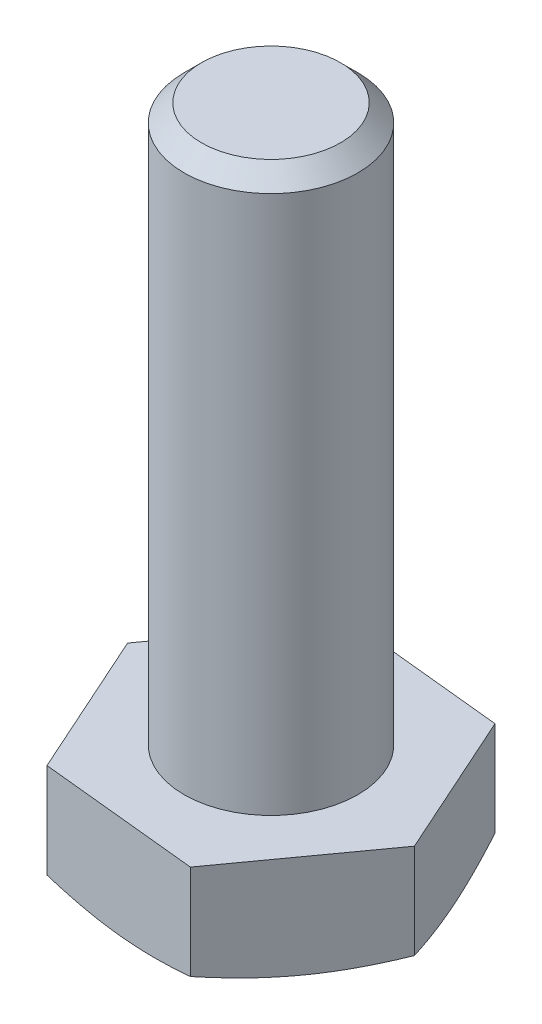
SolidWorks part; units mm, degrees
material "Plain Carbon Steel"
ref_plane "Спереди" through (0, 0, 0) normal (0, 0, 1) x (1, 0, 0)
ref_plane "Сверху" through (0, 0, 0) normal (0, 1, 0) x (1, 0, 0)
ref_plane "Справа" through (0, 0, 0) normal (1, 0, 0) x (0, 0, -1)
sketch "Sketch1" plane through (0, 0, 0) normal (0, 1, 0) x (1, 0, 0)
  circle A0 centre (0, 0) radius 2.5
  dimension "D1" = 5
extrude "Boss-Extrude1" add sketch "Sketch1" along normal blind 16
chamfer "Chamfer1" distance 0.5 angle 45 1 edges at (0, 16, 2.5)
sketch "Sketch2" plane through (0, 0, 0) normal (0, -1, 0) x (1, 0, 0)
  line L1 (4.5951, 0.4675) -> (1.8926, 4.2132)
  line L2 (1.8926, 4.2132) -> (-2.7024, 3.7457)
  line L3 (-2.7024, 3.7457) -> (-4.5951, -0.4675)
  line L4 (-4.5951, -0.4675) -> (-1.8926, -4.2132)
  line L5 (-1.8926, -4.2132) -> (2.7024, -3.7457)
  line L6 (2.7024, -3.7457) -> (4.5951, 0.4675)
  circle A0 centre (0, 0) radius 4 construction
  dimension "D1" = 8
extrude "Boss-Extrude2" add sketch "Sketch2" along normal blind 3.5
sketch "Sketch4" plane through (0, 0, 0) normal (1, 0, 0) x (0, 0, -1)
  line L0 (0, 0) -> (0, -3.5) construction
  line L1 (0, -3.5) -> (2.5, -3.5)
  line L2 (2.5, -3.5) -> (6.1938, -2.1556)
  line L3 (6.1938, -2.1556) -> (6.1938, -4.6468)
  line L4 (6.1938, -4.6468) -> (0, -4.6468)
  line L5 (0, -4.6468) -> (0, -3.5)
  dimension "D1" = 3.5
  dimension "D2" = 2.5
  dimension "D3" = 20
revolve "Cut-Revolve1" cut sketch "Sketch4" angle 360 about L0
